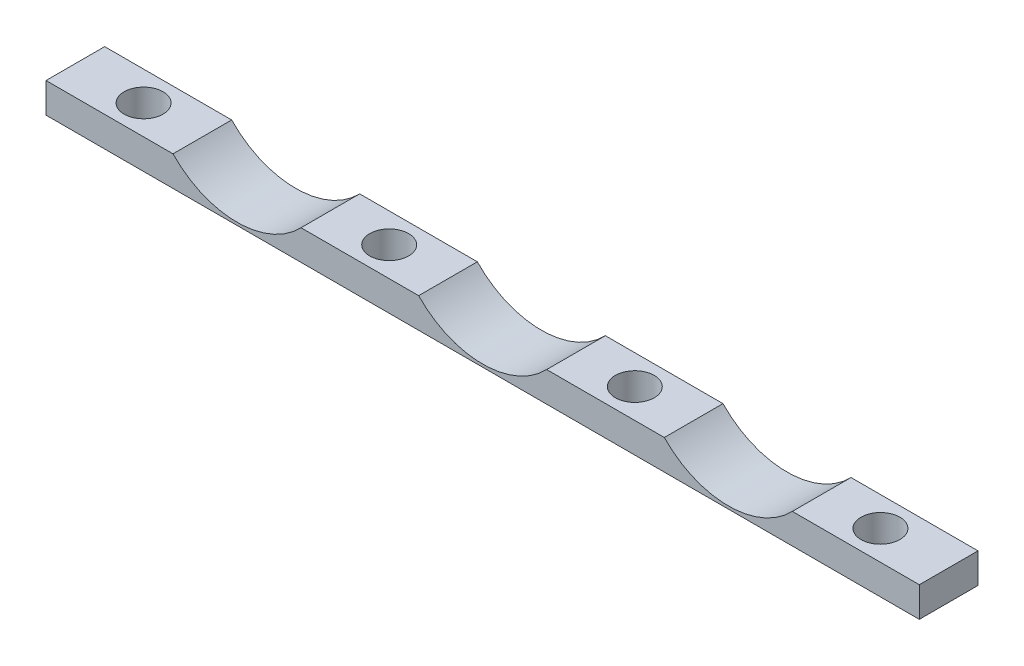
SolidWorks part; units mm, degrees
ref_plane "Front Plane" through (0, 0, 0) normal (0, 0, 1) x (1, 0, 0)
ref_plane "Top Plane" through (0, 0, 0) normal (0, 1, 0) x (1, 0, 0)
ref_plane "Right Plane" through (0, 0, 0) normal (1, 0, 0) x (0, 0, -1)
sketch "Sketch1" plane through (0, 0, 0) normal (0, 0, 1) x (1, 0, 0)
  line L0 (-18.0028, 6) -> (-18.0028, -6) construction
  line L1 (-11.5028, 6) -> (-11.5028, -6) construction
  line L2 (-24.5028, 6) -> (-24.5028, -6) construction
  line L3 (0, 6) -> (0, -6) construction
  line L4 (6.5, 6) -> (6.5, -6) construction
  line L5 (-6.5, 6) -> (-6.5, -6) construction
  line L6 (18.0028, 6) -> (18.0028, -6) construction
  line L7 (24.5028, 6) -> (24.5028, -6) construction
  line L8 (11.5028, 6) -> (11.5028, -6) construction
  line L13 (-18.0028, 6.35) -> (-18.0028, -6.35) construction
  line L18 (-13.3123, -10.5) -> (-4.6904, -10.5)
  line L19 (4.6904, -10.5) -> (13.3123, -10.5)
  line L20 (-15.9528, 6.35) -> (-15.9528, -6.35) construction
  line L21 (-20.0528, 6.35) -> (-20.0528, -6.35) construction
  line L22 (-0.0028, 6.35) -> (-0.0028, -6.35) construction
  line L23 (2.0472, 6.35) -> (2.0472, -6.35) construction
  line L24 (-2.0528, 6.35) -> (-2.0528, -6.35) construction
  line L25 (17.9972, 6.35) -> (17.9972, -6.35) construction
  line L26 (20.0472, 6.35) -> (20.0472, -6.35) construction
  line L27 (15.9472, 6.35) -> (15.9472, -6.35) construction
  line L30 (-32, -12.7) -> (32, -12.7)
  line L31 (-22.6932, -10.5) -> (-32, -10.5)
  line L32 (-32, -10.5) -> (-32, -12.7)
  line L33 (22.6932, -10.5) -> (32, -10.5)
  line L34 (32, -10.5) -> (32, -12.7)
  line L35 (-9.0014, -10.5) -> (-9.0014, 6) construction
  line L36 (9.0014, -10.5) -> (9.0014, 6) construction
  line L37 (27.0014, -10.5) -> (27.0014, 6) construction
  line L38 (-27.0014, -10.5) -> (-27.0014, 6) construction
  arc A0 (-11.5028, 6) -> (-24.5028, 6) centre (-18.0028, 6) ccw construction
  arc A1 (-24.5028, -6) -> (-11.5028, -6) centre (-18.0028, -6) ccw construction
  arc A2 (6.5, 6) -> (-6.5, 6) centre (0, 6) ccw construction
  arc A3 (-6.5, -6) -> (6.5, -6) centre (0, -6) ccw construction
  arc A4 (24.5028, 6) -> (11.5028, 6) centre (18.0028, 6) ccw construction
  arc A5 (11.5028, -6) -> (24.5028, -6) centre (18.0028, -6) ccw construction
  arc A8 (-15.9528, 6.35) -> (-20.0528, 6.35) centre (-18.0028, 6.35) ccw construction
  arc A9 (-20.0528, -6.35) -> (-15.9528, -6.35) centre (-18.0028, -6.35) ccw construction
  arc A10 (2.0472, 6.35) -> (-2.0528, 6.35) centre (-0.0028, 6.35) ccw construction
  arc A11 (-2.0528, -6.35) -> (2.0472, -6.35) centre (-0.0028, -6.35) ccw construction
  arc A12 (20.0472, 6.35) -> (15.9472, 6.35) centre (17.9972, 6.35) ccw construction
  arc A13 (15.9472, -6.35) -> (20.0472, -6.35) centre (17.9972, -6.35) ccw construction
  arc A14 (-22.6932, -10.5) -> (-13.3123, -10.5) centre (-18.0028, -6) ccw
  arc A15 (-4.6904, -10.5) -> (4.6904, -10.5) centre (0, -6) ccw
  arc A16 (13.3123, -10.5) -> (22.6932, -10.5) centre (18.0028, -6) ccw
  arc A17 (-9.0014, 6) -> (-27.0014, 6) centre (-18.0014, 6) ccw construction
  arc A18 (9.0014, 6) -> (27.0014, 6) centre (18.0014, 6) cw construction
  point P3 (-18.0028, 0)
  point P11 (0, 0)
  point P18 (18.0028, 0)
  point P24 (0, 0)
  point P38 (-18.0028, 0)
  point P47 (-0.0028, 0)
  point P54 (17.9972, 0)
  point P59 (-18.0028, -12.5)
  point P67 (0, 0)
  dimension "D3" = 3
  dimension "D1" = 13
  dimension "D2" = 12
  dimension "D4" = 10.5
  dimension "D5" = 18.0028
  dimension "D6" = 0.2
  dimension "D7" = 18
  dimension "D8" = 18
  dimension "D9" = 64
  dimension "D11" = 4.1
  dimension "D12" = 12.7
  dimension "D13" = 3
extrude "Boss-Extrude1" add sketch "Sketch1" along normal blind 4.3
sketch "Sketch2" plane through (0, -10.5, 0) normal (0, 1, 0) x (1, 0, 0)
  line L0 (-32, -2.15) -> (32, -2.15) construction
  line L1 (-32, -4.3) -> (-32, 0) construction
  line L2 (32, -4.3) -> (32, 0) construction
  line L3 (0, 0) -> (0, -4.3) construction
  line L4 (-4.6904, -4.3) -> (4.6904, -4.3) construction
  circle A0 centre (-9, -2.15) radius 1.425
  circle A1 centre (9, -2.15) radius 1.425
  circle A2 centre (-27, -2.15) radius 1.425
  circle A3 centre (27, -2.15) radius 1.425
  dimension "D1" = 2.85
  dimension "D2" = 18
  dimension "D3" = 9
  dimension "D4" = 9
  dimension "D5" = 18
extrude "Cut-Extrude1" cut sketch "Sketch2" against normal through all
